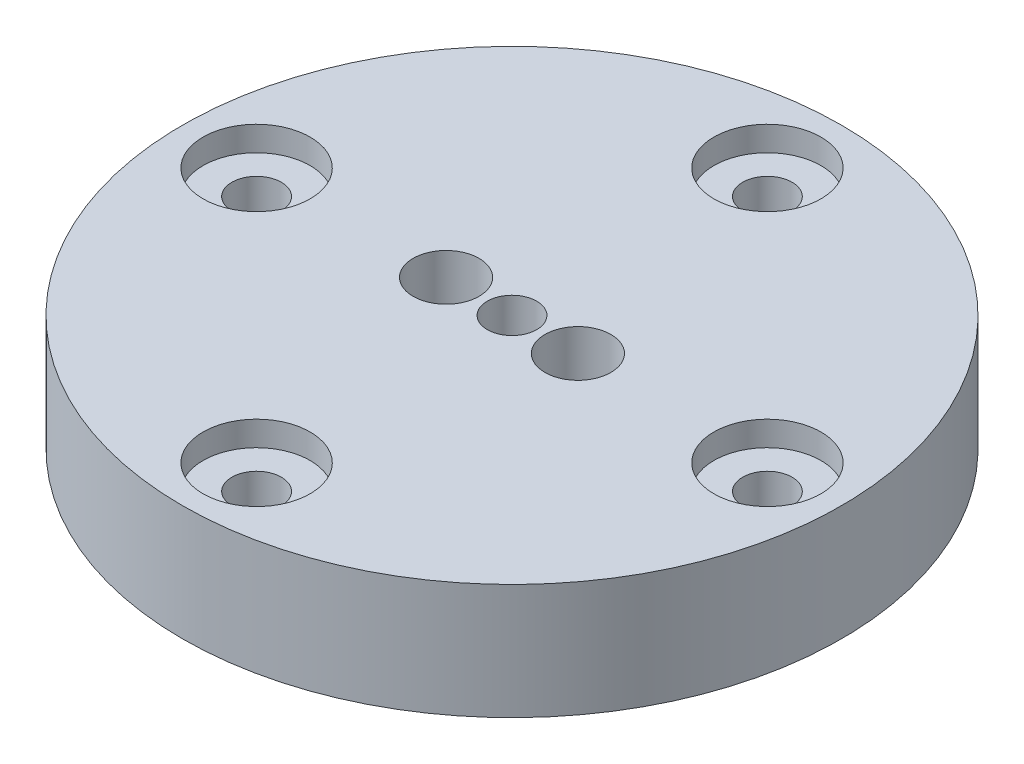
SolidWorks part; units mm, degrees
ref_plane "Front Plane" through (0, 0, 0) normal (0, 0, 1) x (1, 0, 0)
ref_plane "Top Plane" through (0, 0, 0) normal (0, 1, 0) x (1, 0, 0)
ref_plane "Right Plane" through (0, 0, 0) normal (1, 0, 0) x (0, 0, -1)
sketch "Sketch1" plane through (0, 0, 0) normal (0, 1, 0) x (1, 0, 0)
  circle A0 centre (0, 0) radius 15.5 construction
  circle A1 centre (0, 15.5) radius 1.5
  circle A2 centre (15.5, 0) radius 1.5
  circle A3 centre (0, -15.5) radius 1.5
  circle A4 centre (-15.5, 0) radius 1.5
  circle A5 centre (0, 0) radius 20
  circle A6 centre (0, 0) radius 4 construction
  circle A7 centre (-4, 0) radius 2
  circle A8 centre (4, 0) radius 2
  circle A9 centre (0, 0) radius 1.5
  point P14 (0, 0)
  dimension "D1" = 31
  dimension "D2" = 3
  dimension "D4" = 40
  dimension "D5" = 8
  dimension "D6" = 4
  dimension "D7" = 3
  dimension "D3" = 4
extrude "Boss-Extrude1" add sketch "Sketch1" along normal blind 7
sketch "Sketch2" plane through (0, 7, 0) normal (0, 1, 0) x (1, 0, 0)
  circle A0 centre (0, 0) radius 15.5 construction
  circle A1 centre (0, 15.5) radius 3.25
  circle A2 centre (15.5, 0) radius 3.25
  circle A3 centre (0, -15.5) radius 3.25
  circle A4 centre (-15.5, 0) radius 3.25
  point P15 (0, 0)
  dimension "D1" = 6.5
  dimension "D2" = 4
extrude "Cut-Extrude1" cut sketch "Sketch2" against normal blind 1.5
